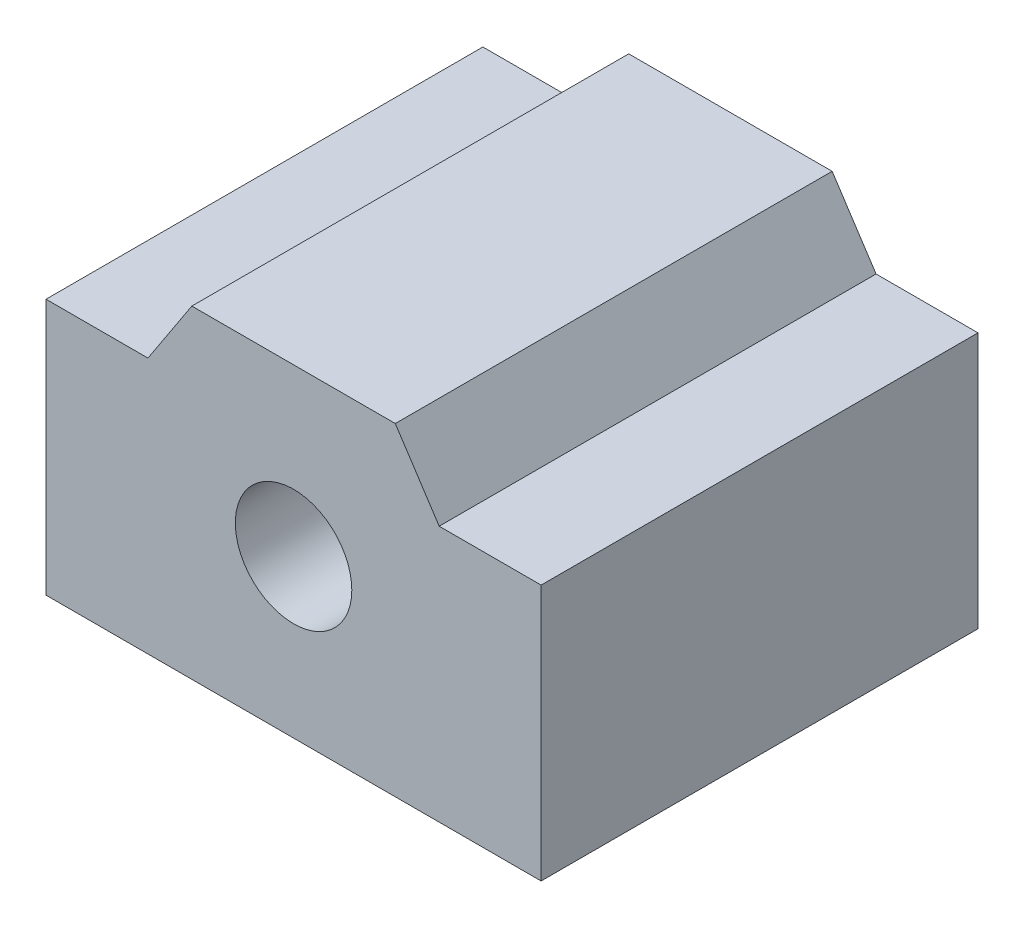
SolidWorks part; units mm, degrees
ref_plane "Front Plane" through (0, 0, 0) normal (0, 0, 1) x (1, 0, 0)
ref_plane "Top Plane" through (0, 0, 0) normal (0, 1, 0) x (1, 0, 0)
ref_plane "Right Plane" through (0, 0, 0) normal (1, 0, 0) x (0, 0, -1)
sketch "Sketch1" plane through (0, 0, 0) normal (0, 1, 0) x (1, 0, 0)
  line L1 (0, 0) -> (34, 0)
  line L2 (0, 0) -> (0, 30)
  line L3 (0, 30) -> (34, 30)
  line L4 (34, 0) -> (34, 30)
  dimension "D1" = 30
  dimension "D2" = 34
extrude "Boss-Extrude1" add sketch "Sketch1" along normal blind 22.2
sketch "Sketch2" plane through (0, 0, 0) normal (0, 0, 1) x (1, 0, 0)
  line L0 (34, 17.6) -> (27, 17.6)
  line L1 (34, 22.2) -> (34, 0) construction
  line L2 (0, 0) -> (34, 0) construction
  line L3 (27, 17.6) -> (23.985, 22.2)
  line L4 (0, 22.2) -> (34, 22.2) construction
  line L5 (23.985, 22.2) -> (34, 22.2)
  line L6 (34, 22.2) -> (34, 17.6)
  line L7 (17, 22.2) -> (17, 0) construction
  line L8 (0, 22.2) -> (0, 17.6)
  line L9 (10.015, 22.2) -> (0, 22.2)
  line L10 (7, 17.6) -> (10.015, 22.2)
  line L11 (0, 17.6) -> (7, 17.6)
  dimension "D1" = 17.6
  dimension "D2" = 7
  dimension "D3" = 5.5
extrude "Cut-Extrude1" cut sketch "Sketch2" against normal through all
sketch "Sketch3" plane through (0, 0, 0) normal (0, 0, 1) x (1, 0, 0)
  line L0 (17, 22.2) -> (17, 0) construction
  line L1 (10.015, 22.2) -> (23.985, 22.2) construction
  line L2 (0, 0) -> (34, 0) construction
  circle A0 centre (17, 10.8) radius 4
  dimension "D1" = 8
  dimension "D2" = 11.4
extrude "Cut-Extrude2" cut sketch "Sketch3" against normal through all
